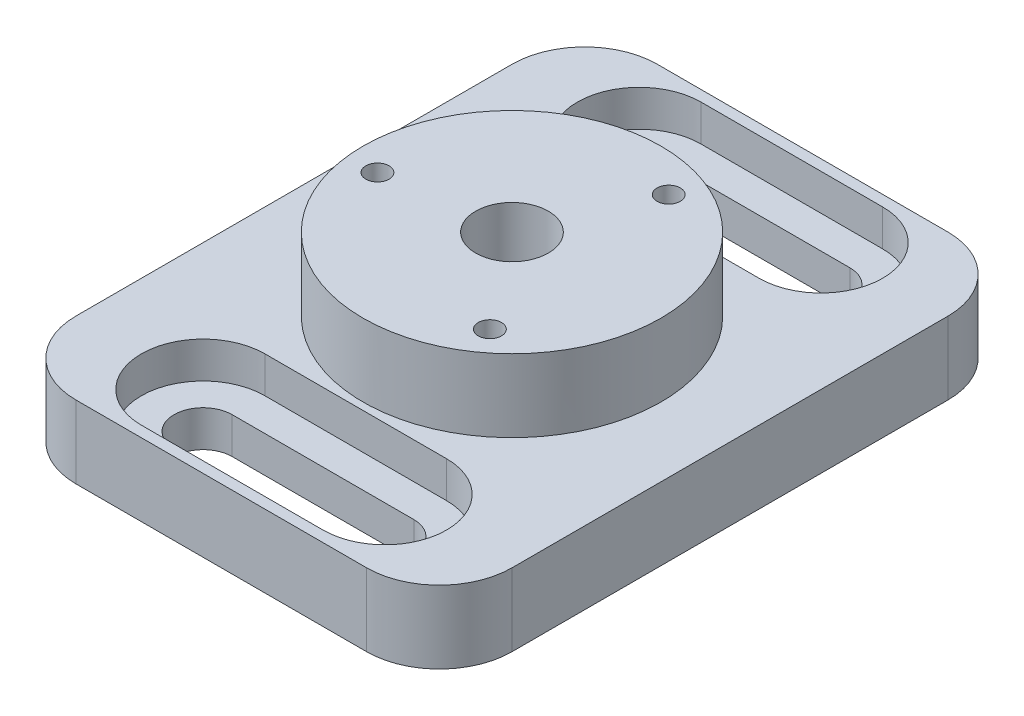
SolidWorks part; units mm, degrees
ref_plane "Front Plane" through (0, 0, 0) normal (0, 0, 1) x (1, 0, 0)
ref_plane "Top Plane" through (0, 0, 0) normal (0, 1, 0) x (1, 0, 0)
ref_plane "Right Plane" through (0, 0, 0) normal (1, 0, 0) x (0, 0, -1)
sketch "Sketch1" plane through (0, 0, 0) normal (0, 1, 0) x (1, 0, 0)
  line L0 (0, 0) -> (0, 20.5) construction
  line L2 (0, 0) -> (6.3143, 15.244) construction
  circle A0 centre (0, 0) radius 20.5
  circle A1 centre (6.3143, 15.244) radius 1.6
  circle A2 centre (10.0446, -13.0903) radius 1.6
  circle A3 centre (-16.3588, -2.1537) radius 1.6
  circle A4 centre (0, 0) radius 5
  point P12 (0, 0)
  dimension "D1" = 3.2
  dimension "D3" = 16.5
  dimension "D4" = 41
  dimension "D6" = 10
  dimension "D2" = 22.5
  dimension "D5" = 3
extrude "Boss-Extrude1" add sketch "Sketch1" along normal blind 20
sketch "Sketch2" plane through (0, 0, 0) normal (0, -1, 0) x (1, 0, 0)
  line L0 (-30, 0) -> (30, 0) construction
  line L5 (-30, -40) -> (30, -40)
  line L6 (-30, -40) -> (-30, 40)
  line L7 (-30, 40) -> (30, 40)
  line L8 (30, -40) -> (30, 40)
  line L9 (-12.5, 30) -> (12.5, 30) construction
  line L10 (-12.5, 34) -> (12.5, 34)
  line L11 (-12.5, 26) -> (12.5, 26)
  line L12 (-12.5, -30) -> (12.5, -30) construction
  line L13 (-12.5, -34) -> (12.5, -34)
  line L14 (-12.5, -26) -> (12.5, -26)
  arc A0 (-12.5, 34) -> (-12.5, 26) centre (-12.5, 30) ccw
  arc A1 (12.5, 26) -> (12.5, 34) centre (12.5, 30) ccw
  arc A2 (-12.5, -34) -> (-12.5, -26) centre (-12.5, -30) cw
  arc A3 (12.5, -26) -> (12.5, -34) centre (12.5, -30) cw
  circle A4 centre (0, 0) radius 20.5 construction
  circle A5 centre (0, 0) radius 20.5
  point P0 (0, 0)
  point P8 (0, 30)
  point P19 (0, -30)
  dimension "D1" = 60
  dimension "D2" = 80
  dimension "D3" = 8
  dimension "D4" = 25
  dimension "D5" = 30
extrude "Boss-Extrude2" add sketch "Sketch2" against normal blind 10
sketch "Sketch3" plane through (0, 10, 0) normal (0, 1, 0) x (1, 0, 0)
  line L35 (-12.5, 30) -> (12.5, 30) construction
  line L36 (-12.5, 38.5) -> (12.5, 38.5)
  line L37 (-12.5, 21.5) -> (12.5, 21.5)
  line L38 (-30, 0) -> (30, 0) construction
  line L39 (-30, 0) -> (30, 0) construction
  line L40 (-12.5, -30) -> (12.5, -30) construction
  line L41 (-12.5, -38.5) -> (12.5, -38.5)
  line L42 (-12.5, -21.5) -> (12.5, -21.5)
  arc A30 (-12.5, 38.5) -> (-12.5, 21.5) centre (-12.5, 30) ccw
  arc A31 (12.5, 21.5) -> (12.5, 38.5) centre (12.5, 30) ccw
  arc A32 (-12.5, -38.5) -> (-12.5, -21.5) centre (-12.5, -30) cw
  arc A33 (12.5, -21.5) -> (12.5, -38.5) centre (12.5, -30) cw
  point P0 (0, 30)
  point P9 (0, -30)
  dimension "D1" = 17
extrude "Cut-Extrude1" cut sketch "Sketch3" against normal blind 5
fillet "Fillet1" radius 10 4 edges at (30, 5, -40) (30, 5, 40) (-30, 5, 40) (-30, 5, -40)
sketch "Sketch4" plane through (0, 0, 0) normal (0, -1, 0) x (1, 0, 0)
  circle A0 centre (10.0446, 13.0903) radius 5
  circle A1 centre (6.3143, -15.244) radius 5
  circle A2 centre (-16.3588, 2.1537) radius 5
  dimension "D1" = 10
extrude "Cut-Extrude2" cut sketch "Sketch4" against normal blind 7
